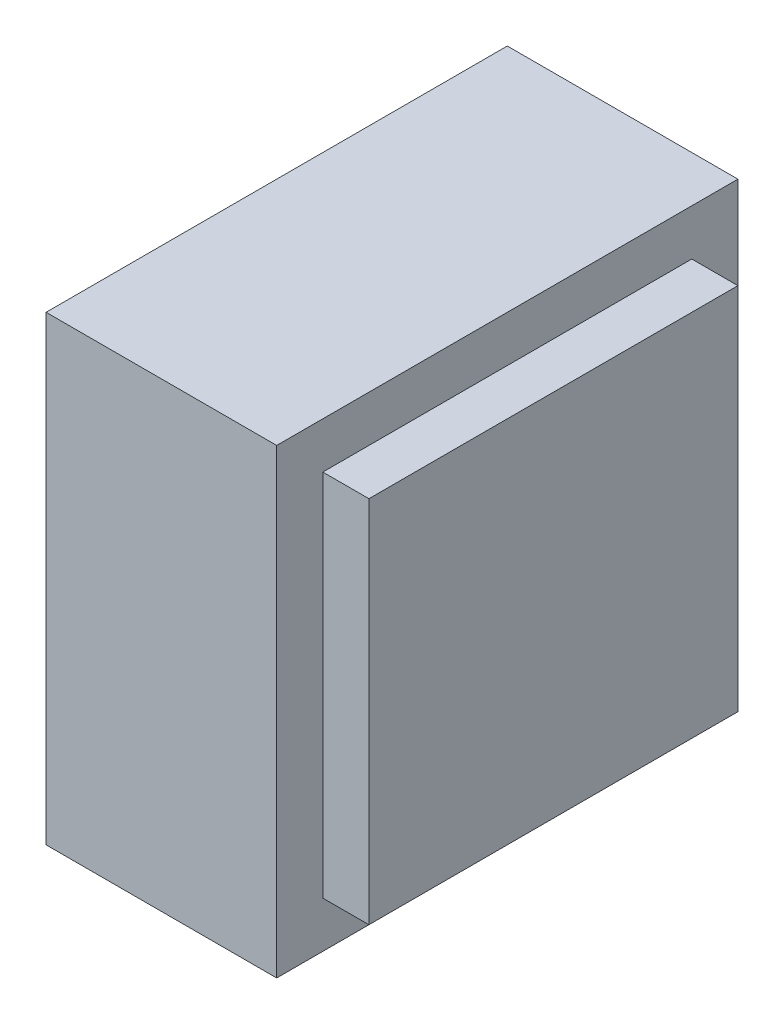
SolidWorks part; units mm, degrees
ref_plane "Front Plane" through (0, 0, 0) normal (0, 0, 1) x (1, 0, 0)
ref_plane "Top Plane" through (0, 0, 0) normal (0, 1, 0) x (1, 0, 0)
ref_plane "Right Plane" through (0, 0, 0) normal (1, 0, 0) x (0, 0, -1)
sketch "Sketch1" plane through (0, 0, 0) normal (1, 0, 0) x (0, 0, -1)
  line L1 (-1, 1) -> (1, 1)
  line L2 (-1, 1) -> (-1, -1)
  line L3 (-1, -1) -> (1, -1)
  line L4 (1, 1) -> (1, -1)
  line L5 (-1, 1) -> (1, -1) construction
  line L6 (-1, -1) -> (1, 1) construction
  point P0 (0, 0)
  dimension "D1" = 2
  dimension "D2" = 2
extrude "Boss-Extrude1" add sketch "Sketch1" along normal blind 1
sketch "Sketch2" plane through (1, 0, 0) normal (1, 0, 0) x (0, 0, -1)
  line L1 (-0.8, 0.8) -> (0.8, 0.8)
  line L2 (-0.8, 0.8) -> (-0.8, -0.8)
  line L3 (-0.8, -0.8) -> (0.8, -0.8)
  line L4 (0.8, 0.8) -> (0.8, -0.8)
  line L5 (-0.8, 0.8) -> (0.8, -0.8) construction
  line L6 (-0.8, -0.8) -> (0.8, 0.8) construction
  point P0 (0, 0)
  dimension "D1" = 1.6
  dimension "D2" = 1.6
extrude "Boss-Extrude2" add sketch "Sketch2" along normal blind 0.2
